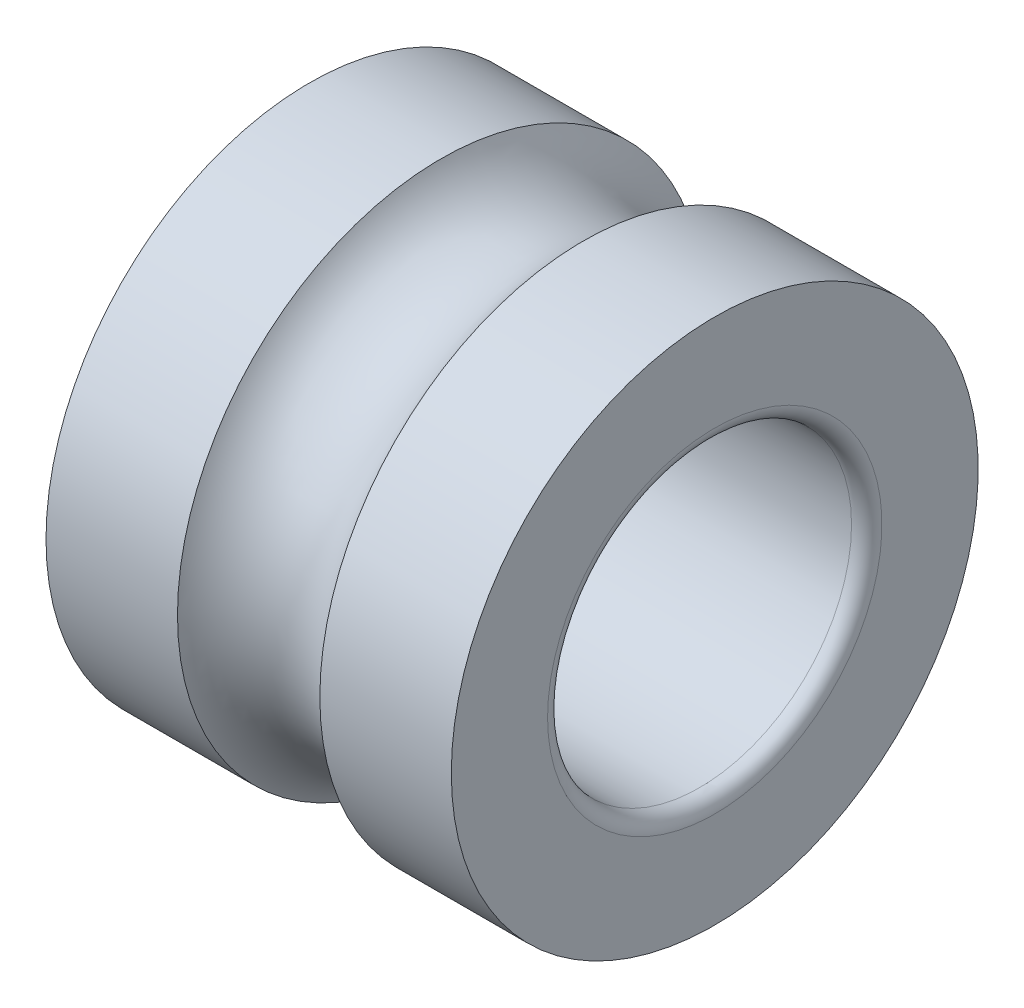
SolidWorks part; units mm, degrees
ref_plane "Front Plane" through (0, 0, 0) normal (0, 0, 1) x (1, 0, 0)
ref_plane "Top Plane" through (0, 0, 0) normal (0, 1, 0) x (1, 0, 0)
ref_plane "Right Plane" through (0, 0, 0) normal (1, 0, 0) x (0, 0, -1)
ref_plane "Plane1" through (0, 0, 0) normal (0, 0, 1) x (1, 0, 0)
sketch "Sketch1" plane through (0, 0, 0) normal (0, 0, 1) x (1, 0, 0)
  line L0 (0.15, 1.5) -> (3.85, 1.5)
  line L1 (4, 1.65) -> (4, 2.6)
  line L2 (4, 2.6) -> (2.7025, 2.6)
  line L3 (1.2975, 2.6) -> (0, 2.6)
  line L4 (0, 2.6) -> (0, 1.65)
  line L5 (50, 0) -> (-50, 0) construction
  arc A0 (0, 1.65) -> (0.15, 1.5) centre (0.15, 1.65) ccw
  arc A1 (3.85, 1.5) -> (4, 1.65) centre (3.85, 1.65) ccw
  arc A2 (2.7025, 2.6) -> (1.2975, 2.6) centre (2, 2.97) cw
revolve "Revolve1" add sketch "Sketch1" angle 360 about L5
